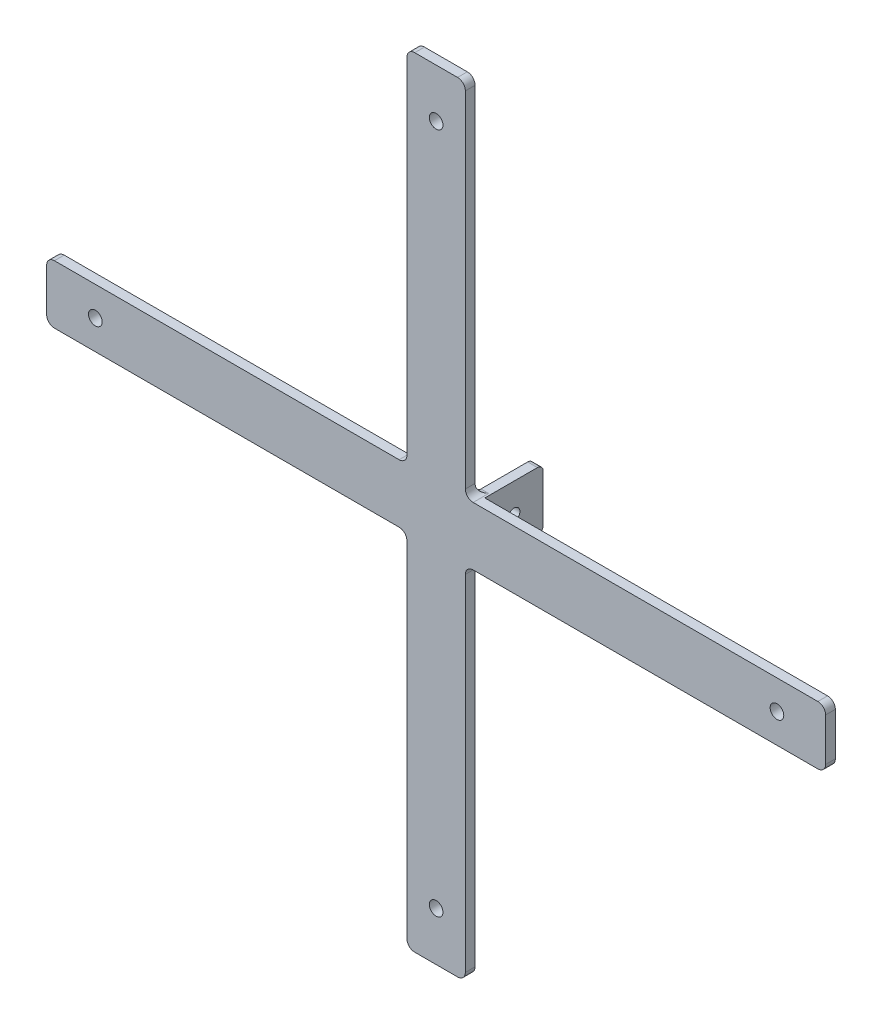
SolidWorks part; units mm, degrees
material "6063-O"
ref_plane "Front" through (0, 0, 0) normal (0, 0, 1) x (1, 0, 0)
ref_plane "Top" through (0, 0, 0) normal (0, 1, 0) x (1, 0, 0)
ref_plane "Right" through (0, 0, 0) normal (1, 0, 0) x (0, 0, -1)
sketch "Sketch1" plane through (0, 0, 0) normal (0, 0, 1) x (1, 0, 0)
  line L1 (-15, 200) -> (15, 200)
  line L2 (-15, 200) -> (-15, -200)
  line L3 (-15, -200) -> (15, -200)
  line L4 (15, 200) -> (15, -200)
  line L5 (-15, 200) -> (15, -200) construction
  line L6 (-15, -200) -> (15, 200) construction
  line L7 (-200, 15) -> (200, 15)
  line L8 (-200, 15) -> (-200, -15)
  line L9 (-200, -15) -> (200, -15)
  line L10 (200, 15) -> (200, -15)
  line L11 (-200, 15) -> (200, -15) construction
  line L12 (-200, -15) -> (200, 15) construction
  point P0 (0, 0)
  point P6 (0, 0)
  dimension "D1" = 200
  dimension "D2" = 200
  dimension "D3" = 30
  dimension "D4" = 30
extrude "Boss-Extrude1" add sketch "Sketch1" along normal blind 5 contours L10 L7 L4 L9 | L2 L7 L4 L1 | L8 L9 L2 L7 | L2 L9 L4 L7 | L9 L2 L3 L4
sketch "Sketch2" plane through (0, 0, 0) normal (0, 0, -1) x (-1, 0, 0)
  line L0 (-15, -15) -> (-200, -15) construction
  line L1 (-15, 15) -> (-20, 15)
  line L2 (-15, 15) -> (-15, -15)
  line L3 (-15, -15) -> (-20, -15)
  line L4 (-20, 15) -> (-20, -15)
  line L5 (200, 15) -> (15, 15) construction
  line L6 (15, -15) -> (20, -15)
  line L7 (15, -15) -> (15, 15)
  line L8 (15, 15) -> (20, 15)
  line L9 (20, -15) -> (20, 15)
  dimension "D1" = 5
  dimension "D2" = 5
extrude "Boss-Extrude2" add sketch "Sketch2" along normal blind 30
sketch "Sketch3" plane through (20, 0, 0) normal (1, 0, 0) x (0, 0, -1)
  line L0 (30, 15) -> (30, -15) construction
  circle A0 centre (15, 0) radius 3
  dimension "D1" = 6
  dimension "D2" = 15
extrude "Cut-Extrude1" cut sketch "Sketch3" against normal through all and the other way through all
sketch "Sketch4" plane through (0, 0, 5) normal (0, 0, 1) x (1, 0, 0)
  circle A0 centre (0, 175) radius 3.5
  circle A1 centre (175, 0) radius 3.5
  circle A2 centre (0, -175) radius 3.5
  circle A3 centre (-175, 0) radius 3.5
  point P11 (0, 0)
  dimension "D1" = 7
  dimension "D2" = 175
  dimension "D3" = 4
extrude "Cut-Extrude2" cut sketch "Sketch4" against normal up to vertex (5 mm away) up to point (0, 0, 0)
fillet "Fillet1" radius 4 12 edges at (200, -15, 2.5) (15, -15, 2.5) (15, -200, 2.5) (-15, -200, 2.5) (-15, -15, 2.5) (-200, -15, 2.5) (-200, 15, 2.5) (-15, 15, 2.5) (15, 200, 2.5) (15, 15, 2.5) (200, 15, 2.5) (-15, 200, 2.5)
fillet "Fillet2" radius 3 4 edges at (17, -15, 0) (17.5, -15, -30) (17, 15, 0) (17.5, 15, -30)
fillet "Fillet3" radius 3 4 edges at (-17, 15, 0) (-17.5, 15, -30) (-17, -15, 0) (-17.5, -15, -30)
